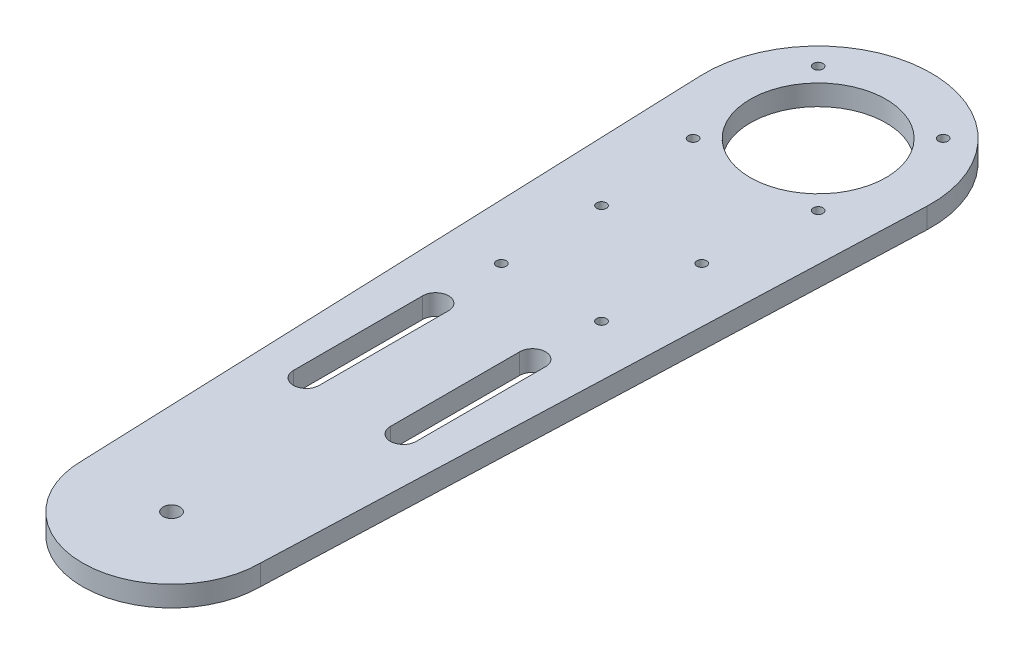
SolidWorks part; units mm, degrees
ref_plane "Front Plane" through (0, 0, 0) normal (0, 0, 1) x (1, 0, 0)
ref_plane "Top Plane" through (0, 0, 0) normal (0, 1, 0) x (1, 0, 0)
ref_plane "Right Plane" through (0, 0, 0) normal (1, 0, 0) x (0, 0, -1)
sketch "Sketch1" plane through (0, 0, 0) normal (0, 1, 0) x (1, 0, 0)
  line L0 (27.5, 0) -> (34.9753, 198.6841)
  line L1 (-27.5, 0) -> (-34.9753, 198.6841)
  arc A0 (-27.5, 0) -> (27.5, 0) centre (0, 0) ccw
  arc A3 (34.9753, 198.6841) -> (-34.9753, 198.6841) centre (0, 200) ccw
  dimension "D1" = 55
  dimension "D3" = 200
  dimension "D2" = 70
extrude "Boss-Extrude1" add sketch "Sketch1" along normal blind 6.35
sketch "Sketch2" plane through (0, 6.35, 0) normal (0, 1, 0) x (1, 0, 0)
  circle A0 centre (0, 0) radius 2.6
  dimension "D1" = 5.2
extrude "Cut-Extrude1" cut sketch "Sketch2" against normal through all
sketch "Esquisse4" plane through (0, 6.35, 0) normal (0, 1, 0) x (1, 0, 0)
  circle A0 centre (0, 200) radius 35
  arc A1 (34.9753, 198.6841) -> (-34.9753, 198.6841) centre (0, 200) ccw construction
sketch "Esquisse3" plane through (0, 6.35, 0) normal (0, 1, 0) x (1, 0, 0)
  circle A1 centre (0, 200) radius 21
  dimension "D1" = 42
extrude "Enlèv. mat.-Extru.2" cut sketch "Esquisse3" against normal through all
sketch "Esquisse5" plane through (0, 6.35, 0) normal (0, 1, 0) x (1, 0, 0)
  circle A0 centre (0, 200) radius 27.35
  dimension "D1" = 54.7
sketch "Esquisse7" plane through (0, 6.35, 0) normal (0, 1, 0) x (1, 0, 0)
  line L0 (-19.3394, 180.6606) -> (19.3394, 180.6606) construction
  line L1 (19.3394, 180.6606) -> (19.3394, 219.3394) construction
  line L2 (19.3394, 219.3394) -> (-19.3394, 219.3394) construction
  line L3 (-19.3394, 219.3394) -> (-19.3394, 180.6606) construction
  circle A0 centre (-19.3394, 219.3394) radius 1.5
  circle A1 centre (0, 200) radius 27.35 construction
  circle A2 centre (19.3394, 219.3394) radius 1.5
  circle A3 centre (19.3394, 180.6606) radius 1.5
  circle A4 centre (-19.3394, 180.6606) radius 1.5
  point P12 (0, 180.6606)
  dimension "D1" = 3
extrude "Enlèv. mat.-Extru.3" cut sketch "Esquisse7" against normal through all
sketch "Esquisse10" plane through (0, 0, 0) normal (1, 0, 0) x (0, 0, -1)
  line L0 (200, 30.779) -> (200, -18.079) construction
  point P4 (200, 6.35)
sketch "Esquisse8" plane through (0, 6.35, 0) normal (0, 1, 0) x (1, 0, 0)
  line L0 (18.4733, 182.1606) -> (20.2054, 182.1606)
  line L1 (20.2054, 182.1606) -> (21.0714, 180.6606)
  line L2 (21.0714, 180.6606) -> (20.2054, 179.1606)
  line L3 (20.2054, 179.1606) -> (18.4733, 179.1606)
  line L4 (18.4733, 179.1606) -> (17.6073, 180.6606)
  line L5 (17.6073, 180.6606) -> (18.4733, 182.1606)
  circle A1 centre (19.3394, 180.6606) radius 1.5 construction
extrude "Enlèv. mat.-Extru.5" [suppressed] cut sketch "Esquisse8" against normal through all
pattern_circular "Répétition circulaire1" [suppressed] count 4 over 360 about axis through (0, 30.779, -200) along (0, -1, 0)
sketch "Sketch4" plane through (0, 6.35, 0) normal (0, 1, 0) x (1, 0, 0)
  line L0 (-15, 56.7) -> (-15, 96.7) construction
  line L1 (-19, 56.7) -> (-19, 96.7)
  line L2 (-11, 56.7) -> (-11, 96.7)
  line L3 (15, 56.7) -> (15, 96.7) construction
  line L4 (11, 56.7) -> (11, 96.7)
  line L5 (19, 56.7) -> (19, 96.7)
  arc A0 (-19, 56.7) -> (-11, 56.7) centre (-15, 56.7) ccw
  arc A1 (-11, 96.7) -> (-19, 96.7) centre (-15, 96.7) ccw
  arc A2 (11, 56.7) -> (19, 56.7) centre (15, 56.7) ccw
  arc A3 (19, 96.7) -> (11, 96.7) centre (15, 96.7) ccw
  point P4 (-15, 76.7)
  point P9 (15, 76.7)
  dimension "D1" = 4
extrude "Cut-Extrude3" cut sketch "Sketch4" against normal through all
sketch "Sketch5" plane through (0, 0, 0) normal (0, -1, 0) x (1, 0, 0)
  circle A0 centre (15.5, -117.5) radius 1.5
  circle A1 centre (15.5, -148.5) radius 1.5
  circle A2 centre (-15.5, -148.5) radius 1.5
  circle A3 centre (-15.5, -117.5) radius 1.5
  dimension "D1" = 3
extrude "Cut-Extrude4" cut sketch "Sketch5" against normal through all
